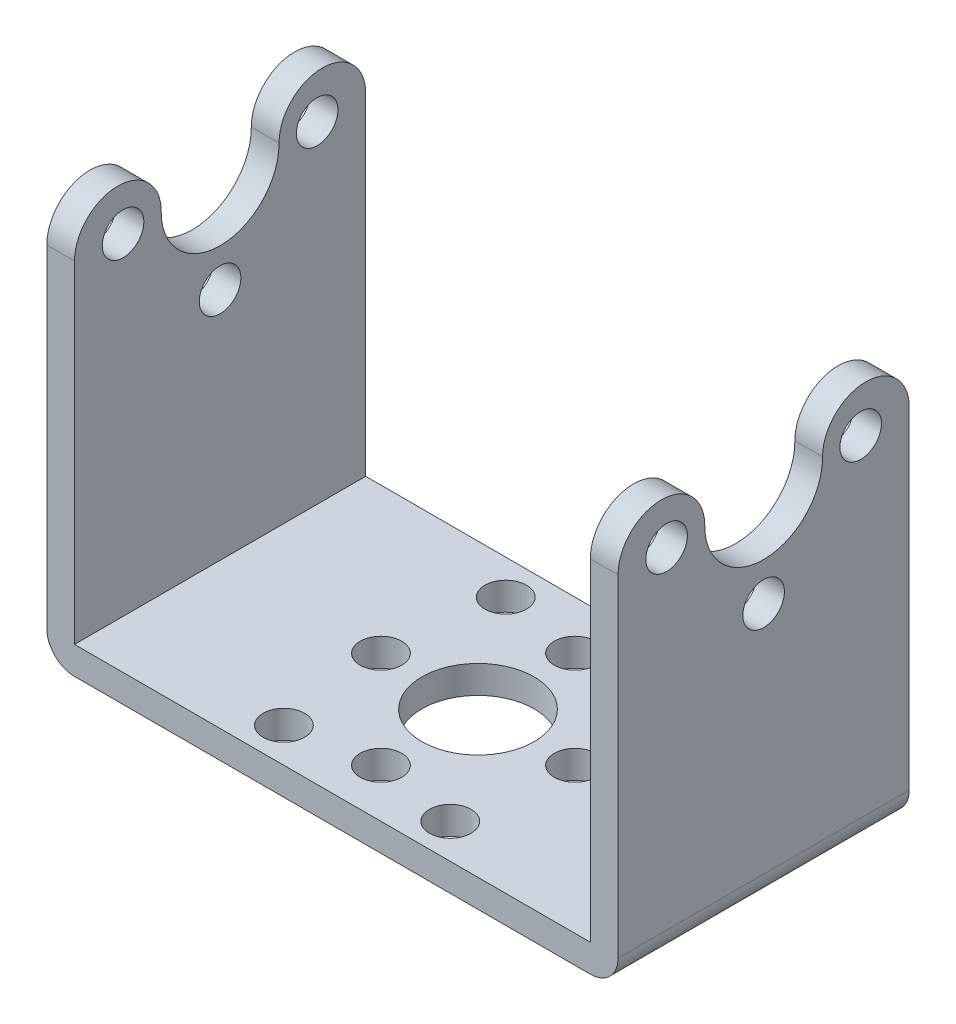
SolidWorks part; units mm, degrees
material "6061 Alloy"
ref_plane "Front Plane" through (0, 0, 0) normal (0, 0, 1) x (1, 0, 0)
ref_plane "Top Plane" through (0, 0, 0) normal (0, 1, 0) x (1, 0, 0)
ref_plane "Right Plane" through (0, 0, 0) normal (1, 0, 0) x (0, 0, -1)
sketch "Sketch1" plane through (0, 0, 0) normal (0, 1, 0) x (1, 0, 0)
  line L0 (-18.6, 10.5) -> (-18.6, -10.5) construction
  line L1 (-20.6, -10.5) -> (20.6, -10.5)
  line L2 (-20.6, -10.5) -> (-20.6, 10.5)
  line L3 (-20.6, 10.5) -> (20.6, 10.5)
  line L4 (20.6, -10.5) -> (20.6, 10.5)
  line L5 (18.6, 10.5) -> (18.6, -10.5) construction
  line L6 (-6, 10.5) -> (-6, -10.5) construction
  line L7 (0, 10.5) -> (0, -10.5) construction
  line L8 (6, 10.5) -> (6, -10.5) construction
  line L9 (-20.6, 8) -> (20.6, 8) construction
  line L10 (-20.6, 0) -> (20.6, 0) construction
  line L11 (-20.6, -8) -> (20.6, -8) construction
  circle A0 centre (0, 0) radius 7 construction
  circle A1 centre (0, 0) radius 4.05
  circle A2 centre (0, 7) radius 1.5
  circle A3 centre (7, 0) radius 1.5
  circle A4 centre (0, -7) radius 1.5
  circle A5 centre (-7, 0) radius 1.5
  circle A7 centre (6, -8) radius 1.5
  circle A8 centre (6, 8) radius 1.5
  circle A9 centre (-6, 8) radius 1.5
  circle A10 centre (-6, -8) radius 1.5
  point P4 (0, 10.5)
  point P6 (-20.6, 0)
  dimension "D5" = 14
  dimension "D6" = 8.1
  dimension "D7" = 3
  dimension "D8" = 3
  dimension "D9" = 3
  dimension "D10" = 3
  dimension "D15" = 3
  dimension "D16" = 3
  dimension "D17" = 3
  dimension "D18" = 3
  dimension "D1" = 41.2
  dimension "D2" = 2
  dimension "D3" = 2
  dimension "D4" = 21
  dimension "D11" = 6
  dimension "D12" = 6
  dimension "D13" = 8
  dimension "D14" = 8
extrude "Boss-Extrude1" add sketch "Sketch1" along normal blind 2
sketch "Sketch2" plane through (0, 2, 0) normal (0, 1, 0) x (1, 0, 0)
  line L0 (-20.6, -10.5) -> (20.6, -10.5) construction
  line L1 (-20.6, 10.5) -> (-18.6, 10.5)
  line L2 (-20.6, 10.5) -> (-20.6, -10.5)
  line L3 (-20.6, -10.5) -> (-18.6, -10.5)
  line L4 (-18.6, 10.5) -> (-18.6, -10.5)
  line L6 (20.6, 10.5) -> (18.6, 10.5)
  line L7 (20.6, 10.5) -> (20.6, -10.5)
  line L8 (20.6, -10.5) -> (18.6, -10.5)
  line L9 (18.6, 10.5) -> (18.6, -10.5)
  dimension "D1" = 2
  dimension "D2" = 2
extrude "Boss-Extrude2" add sketch "Sketch2" along normal blind 28.2
sketch "Sketch3" plane through (-20.6, 0, 0) normal (-1, 0, 0) x (0, 0, 1)
  line L0 (-10.5, 30.2) -> (18.4363, 30.2) construction
  line L1 (-10.5, 0) -> (18.4363, 0) construction
  line L2 (-10.5, 25.9) -> (10.5, 25.9) construction
  line L3 (-10.5, 30.2) -> (-10.5, 0) construction
  line L4 (10.5, 30.2) -> (10.5, 0) construction
  line L5 (-10.5, 25.9) -> (-4.25, 25.9) construction
  line L6 (-10.5, 2) -> (15.4935, 2) construction
  circle A0 centre (0, 25.9) radius 7 construction
  circle A1 centre (-7, 25.9) radius 1.5
  circle A2 centre (0, 18.9) radius 1.5
  circle A3 centre (7, 25.9) radius 1.5
  circle A4 centre (0, 25.9) radius 4.25
  dimension "D3" = 14
  dimension "D4" = 3
  dimension "D5" = 3
  dimension "D6" = 3
  dimension "D7" = 8.5
  dimension "D1" = 30.2
  dimension "D2" = 4.3
extrude "Cut-Extrude1" cut sketch "Sketch3" against normal through all
sketch "Sketch4" plane through (-20.6, 0, 0) normal (-1, 0, 0) x (0, 0, 1)
  line L0 (-8.4994, 25.9441) -> (10.6775, 25.9441) construction
  line L1 (-10.5, 30.2) -> (-10.5, 0) construction
  line L2 (10.5, 30.2) -> (10.5, 0) construction
  line L3 (-10.5, 25.9441) -> (-10.5, 30.2)
  line L4 (-10.5, 30.2) -> (10.5, 30.2)
  line L5 (10.5, 30.2) -> (10.5, 25.9441)
  circle A0 centre (-7, 25.9) radius 1.5 construction
  arc A1 (-10.5, 25.9441) -> (-4.2498, 25.9441) centre (-7.3749, 25.9441) cw
  circle A2 centre (0, 25.9) radius 4.25 construction
  arc A3 (10.5, 25.9441) -> (4.2498, 25.9441) centre (7.3749, 25.9441) ccw
  arc A5 (-4.2498, 25.9441) -> (4.2498, 25.9441) centre (0, 25.9441) ccw
extrude "Cut-Extrude2" cut sketch "Sketch4" against normal through all
fillet "Fillet1" radius 2 2 edges at (-20.6, 0, 0) (20.6, 0, 0)
